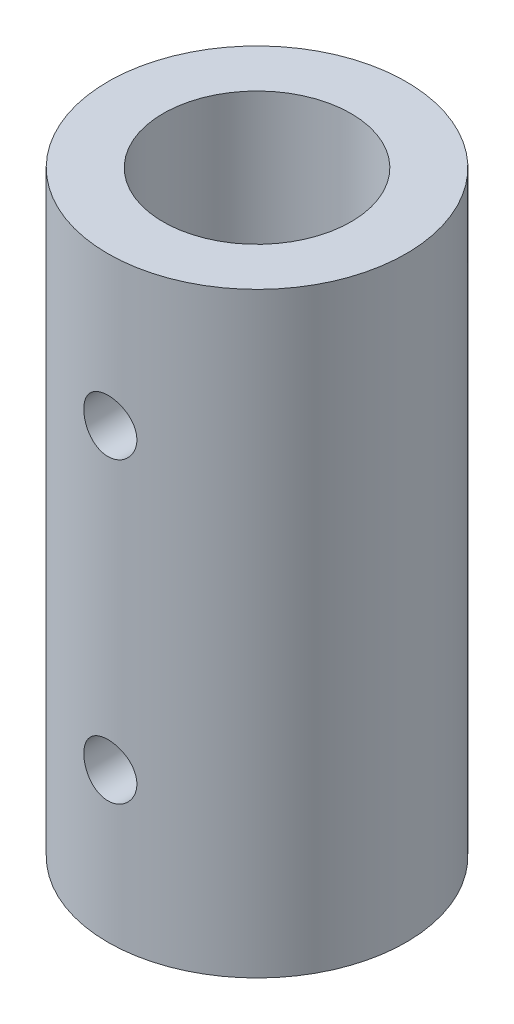
SolidWorks part; units mm, degrees
material "Brass"
ref_plane "Front Plane" through (0, 0, 0) normal (0, 0, 1) x (1, 0, 0)
ref_plane "Top Plane" through (0, 0, 0) normal (0, 1, 0) x (1, 0, 0)
ref_plane "Right Plane" through (0, 0, 0) normal (1, 0, 0) x (0, 0, -1)
sketch "Sketch1" plane through (0, 0, 0) normal (0, 1, 0) x (1, 0, 0)
  circle A0 centre (0, 0) radius 6.35
  dimension "D1" = 12.7
extrude "Boss-Extrude1" add sketch "Sketch1" along normal blind 25.4 contours A0
sketch "Sketch3" plane through (0, 0, 0) normal (0, -1, 0) x (1, 0, 0)
  circle A0 centre (0, 0) radius 4
  dimension "D1" = 8
extrude "Cut-Extrude2" cut sketch "Sketch3" against normal blind 12.7 and the other way through all contours A0
ref_plane "Plane1" through (0, 0, 6.35) normal (0, 0, 1) x (1, 0, 0)
sketch "Sketch6" plane through (0, 0, 0) normal (0, -1, 0) x (-1, 0, 0)
  circle A0 centre (0, 0) radius 4.0005
extrude "Cut-Extrude5" cut sketch "Sketch6" against normal through all
sketch "Sketch4" plane through (0, 0, 6.35) normal (0, 0, 1) x (1, 0, 0)
  line L0 (6.35, 25.4) -> (-6.35, 25.4) construction
  line L1 (-6.35, 0) -> (6.35, 0) construction
  line L2 (0, 0) -> (0, 25.4) construction
  circle A0 centre (0, 6.35) radius 1.1303
  circle A1 centre (0, 19.05) radius 1.1303
  point P11 (-1.3752, 19.05)
  point P12 (2.3357, 6.35)
  point P13 (0, 0)
  dimension "D1" = 2.2606
  dimension "D2" = 6.35
  dimension "D3" = 6.35
extrude "Cut-Extrude3" cut sketch "Sketch4" against normal up to next
sketch "Sketch5" [suppressed] plane through (0, 0, 0) normal (0, -1, 0) x (1, 0, 0)
  circle A0 centre (0, 0) radius 4.0005
  circle A1 centre (0, 0) radius 4.0005 construction
  point P3 (0, 0)
extrude "Cut-Extrude4" [suppressed] cut sketch "Sketch5" against normal through all
